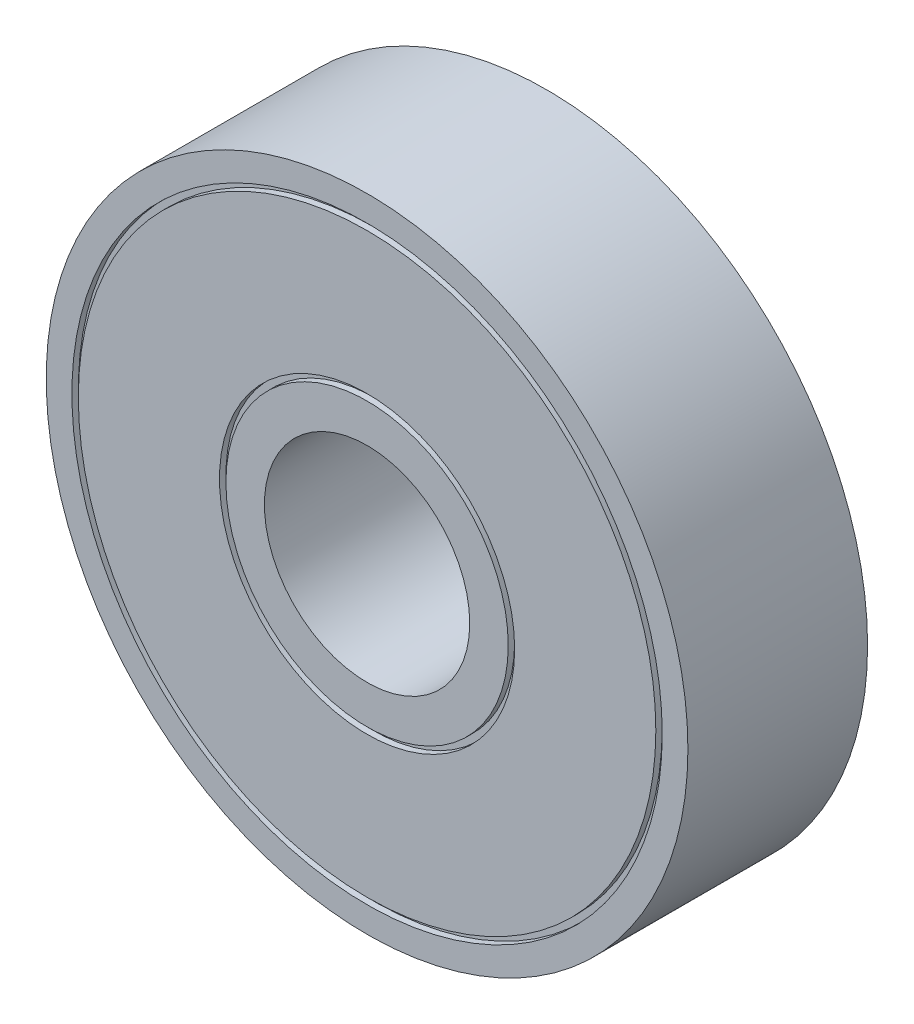
SolidWorks part; units mm, degrees
material "ASTM A36 Aço"
ref_plane "Plano frontal" through (0, 0, 0) normal (0, 0, 1) x (1, 0, 0)
ref_plane "Plano superior" through (0, 0, 0) normal (0, 1, 0) x (1, 0, 0)
ref_plane "Plano direito" through (0, 0, 0) normal (1, 0, 0) x (0, 0, -1)
sketch "Esboço1" plane through (0, 0, 0) normal (0, 0, 1) x (1, 0, 0)
  circle A0 centre (0, 0) radius 4
  circle A1 centre (0, 0) radius 12.5
  dimension "D1" = 8
  dimension "D2" = 25
extrude "Ressalto-extrusão1" add sketch "Esboço1" along normal mid plane 7
sketch "Esboço2" plane through (0, 0, 3.5) normal (0, 0, 1) x (1, 0, 0)
  circle A0 centre (0, 0) radius 11.5
  circle A1 centre (0, 0) radius 12.5
  circle A2 centre (0, 0) radius 12.5
  circle A3 centre (0, 0) radius 11.25
  circle A4 centre (0, 0) radius 5.75
  circle A5 centre (0, 0) radius 5.5
  circle A6 centre (0, 0) radius 5.5
  dimension "D1" = 0
  dimension "D2" = 1.5
  dimension "D3" = 0.25
  dimension "D4" = 1
  dimension "D5" = 0.25
extrude "Corte-extrusão1" cut sketch "Esboço2" against normal blind 0.25 contours A4 A6 | A0 A3
mirror "Espelhar1" about plane through (0, 0, 0) normal (0, 0, 1) of "Corte-extrusão1"
